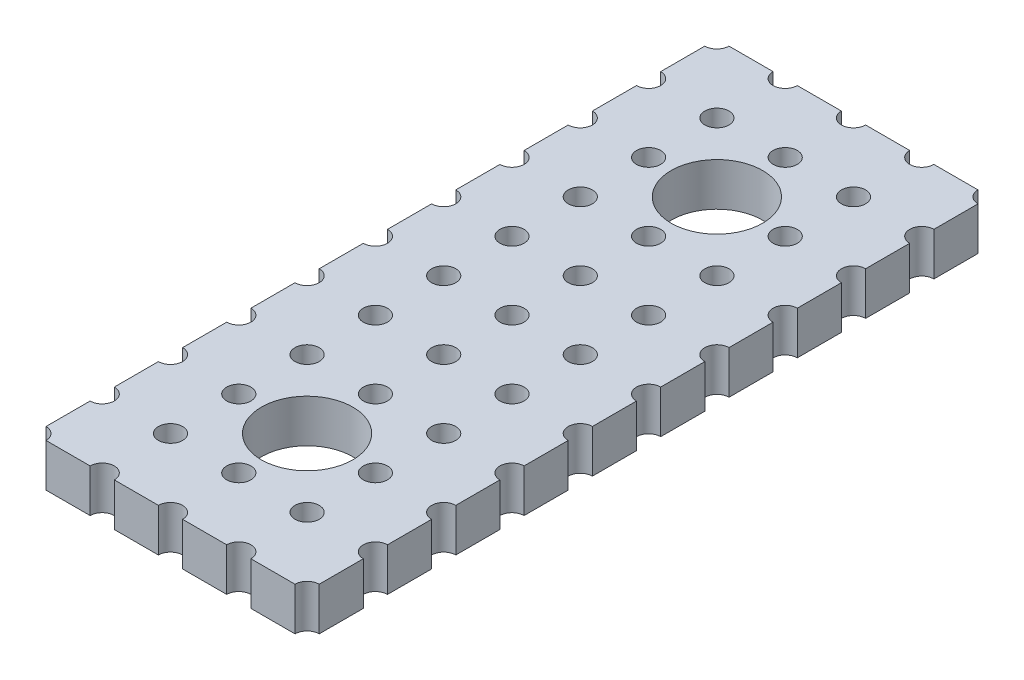
SolidWorks part; units mm, degrees
ref_plane "Plan de face" through (0, 0, 0) normal (0, 0, 1) x (1, 0, 0)
ref_plane "Plan de dessus" through (0, 0, 0) normal (0, 1, 0) x (1, 0, 0)
ref_plane "Plan de droite" through (0, 0, 0) normal (1, 0, 0) x (0, 0, -1)
sketch "Esquisse1" plane through (0, 0, 0) normal (0, 1, 0) x (1, 0, 0)
  line L1 (-3.8847, 3.5299) -> (6.2753, 3.5299)
  line L2 (-3.8847, 3.5299) -> (-3.8847, -21.8701)
  line L3 (-3.8847, -21.8701) -> (6.2753, -21.8701)
  line L4 (6.2753, 3.5299) -> (6.2753, -21.8701)
  dimension "D1" = 10.16
  dimension "D2" = 25.4
extrude "Boss.-Extru.1" add sketch "Esquisse1" along normal blind 1.6
sketch "Esquisse2" plane through (0, 1.6, 0) normal (0, 1, 0) x (1, 0, 0)
  circle A0 centre (-3.8847, 3.5299) radius 0.45
  circle A1 centre (-1.3447, 3.5299) radius 0.45
  circle A2 centre (1.1953, 3.5299) radius 0.45
  circle A3 centre (3.7353, 3.5299) radius 0.45
  circle A4 centre (-1.3447, 0.9899) radius 0.45
  circle A5 centre (1.1953, 0.9899) radius 0.45
  circle A6 centre (3.7353, 0.9899) radius 0.45
  circle A7 centre (-1.3447, -1.5501) radius 0.45
  circle A8 centre (1.1953, -1.5501) radius 0.45
  circle A9 centre (3.7353, -1.5501) radius 0.45
  circle A10 centre (-1.3447, -4.0901) radius 0.45
  circle A11 centre (1.1953, -4.0901) radius 0.45
  circle A12 centre (3.7353, -4.0901) radius 0.45
  circle A13 centre (-1.3447, -6.6301) radius 0.45
  circle A14 centre (1.1953, -6.6301) radius 0.45
  circle A15 centre (3.7353, -6.6301) radius 0.45
  circle A16 centre (-1.3447, -9.1701) radius 0.45
  circle A17 centre (1.1953, -9.1701) radius 0.45
  circle A18 centre (3.7353, -9.1701) radius 0.45
  circle A19 centre (-1.3447, -11.7101) radius 0.45
  circle A20 centre (1.1953, -11.7101) radius 0.45
  circle A21 centre (3.7353, -11.7101) radius 0.45
  circle A22 centre (-1.3447, -14.2501) radius 0.45
  circle A23 centre (1.1953, -14.2501) radius 0.45
  circle A24 centre (3.7353, -14.2501) radius 0.45
  circle A25 centre (-3.8847, 0.9899) radius 0.45
  circle A26 centre (-3.8847, -1.5501) radius 0.45
  circle A27 centre (-3.8847, -4.0901) radius 0.45
  circle A28 centre (-3.8847, -6.6301) radius 0.45
  circle A29 centre (-3.8847, -9.1701) radius 0.45
  circle A30 centre (-3.8847, -11.7101) radius 0.45
  circle A31 centre (-3.8847, -14.2501) radius 0.45
  circle A32 centre (6.2753, 3.5299) radius 0.45
  circle A33 centre (6.2753, 0.9899) radius 0.45
  circle A34 centre (6.2753, -1.5501) radius 0.45
  circle A35 centre (6.2753, -4.0901) radius 0.45
  circle A36 centre (6.2753, -6.6301) radius 0.45
  circle A37 centre (6.2753, -9.1701) radius 0.45
  circle A38 centre (6.2753, -11.7101) radius 0.45
  circle A39 centre (6.2753, -14.2501) radius 0.45
  circle A40 centre (-3.8847, -16.7901) radius 0.45
  circle A41 centre (-1.3447, -16.7901) radius 0.45
  circle A42 centre (1.1953, -16.7901) radius 0.45
  circle A43 centre (3.7353, -16.7901) radius 0.45
  circle A44 centre (6.2753, -16.7901) radius 0.45
  circle A45 centre (-3.8847, -19.3301) radius 0.45
  circle A46 centre (-1.3447, -19.3301) radius 0.45
  circle A47 centre (1.1953, -19.3301) radius 0.45
  circle A48 centre (3.7353, -19.3301) radius 0.45
  circle A49 centre (6.2753, -19.3301) radius 0.45
  circle A50 centre (-3.8847, -21.8701) radius 0.45
  circle A51 centre (-1.3447, -21.8701) radius 0.45
  circle A52 centre (1.1953, -21.8701) radius 0.45
  circle A53 centre (3.7353, -21.8701) radius 0.45
  circle A54 centre (6.2753, -21.8701) radius 0.45
  dimension "D1" = 0.9
  dimension "D4" = 5
  dimension "D5" = 11
extrude "Enlèv. mat.-Extru.1" cut sketch "Esquisse2" against normal through all
hole_wizard "Dégagement M31" positions "Esquisse3" profile "Esquisse4" hole size "M3" standard "ISO" end condition through all
sketch "Esquisse3" plane through (0, 1.6, 0) normal (0, 1, 0) x (1, 0, 0)
  circle A0 centre (1.1953, -16.7901) radius 0.45 construction
  point P0 (1.1953, -16.7901)
  point P8 (1.1953, -1.5501)
sketch "Esquisse4" plane through (1.1953, 1.6, 16.7901) normal (1, 0, 0) x (0, 0, 1)
  line L0 (0, 0) -> (0, 1.6)
  line L1 (0, 1.6) -> (1.7, 1.6)
  line L2 (1.7, 1.6) -> (1.7, 0)
  line L5 (1.7, 0) -> (0, 0)
  line L11 (0, -6.35) -> (0, 107.95) construction
  dimension "Diamètre du perçage jusqu'au prochain" = 3.4
  dimension "Profondeur du perçage jusqu'au prochain" = 1.6
